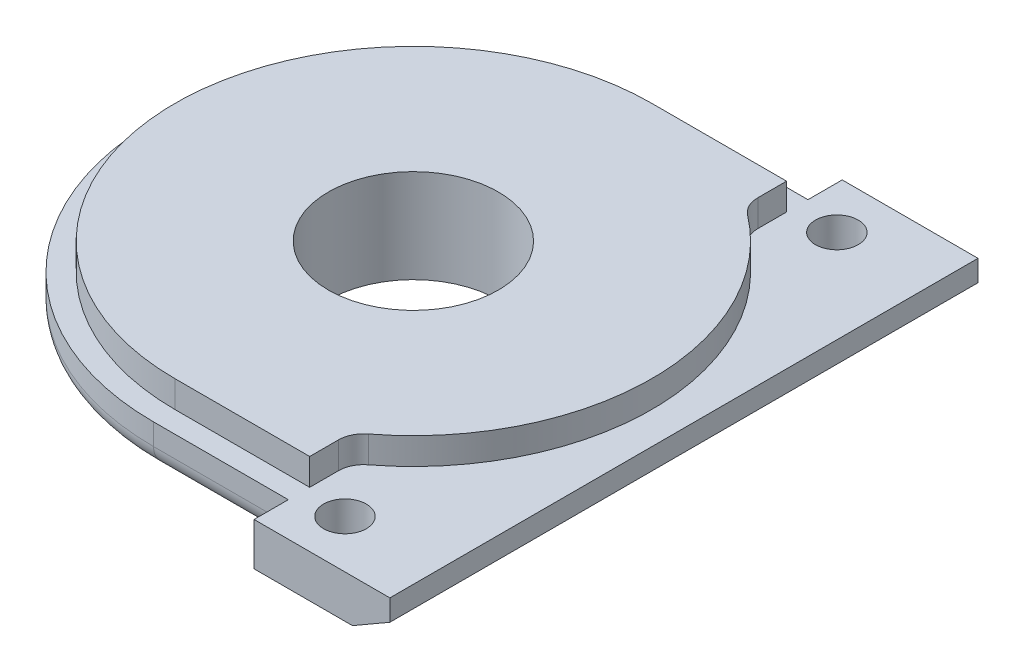
SolidWorks part; units mm, degrees
material "6061-T6 (SS)"
ref_plane "Front Plane" through (0, 0, 0) normal (0, 0, 1) x (1, 0, 0)
ref_plane "Top Plane" through (0, 0, 0) normal (0, 1, 0) x (1, 0, 0)
ref_plane "Right Plane" through (0, 0, 0) normal (1, 0, 0) x (0, 0, -1)
sketch "Sketch1" plane through (0, 0, 0) normal (0, 1, 0) x (1, 0, 0)
  line L0 (-13.2912, 20.8898) -> (-0.69, 20.8898)
  line L5 (-13.2912, -23.7056) -> (-0.69, -23.7056)
  line L7 (-0.69, -23.7056) -> (-0.69, -28.9079)
  line L8 (-0.69, -28.9079) -> (12.01, -28.9079)
  line L9 (-0.69, 20.8898) -> (-0.69, 26.0921)
  line L10 (12.01, -28.9079) -> (12.01, 26.0921)
  line L11 (12.01, 26.0921) -> (-0.69, 26.0921)
  arc A0 (-13.2912, 20.8898) -> (-13.2912, -23.7056) centre (-13.2912, -1.4079) ccw
extrude "Boss-Extrude1" add sketch "Sketch1" along normal blind 4
sketch "Sketch2" plane through (0, 4, 0) normal (0, 1, 0) x (1, 0, 0)
  line L4 (-13.2912, 20.8898) -> (-0.69, 20.8898)
  line L5 (-0.69, 20.8898) -> (-0.69, 16.9877)
  line L6 (-13.2912, -23.7056) -> (-0.69, -23.7056)
  line L7 (-0.69, -23.7056) -> (-0.69, -19.8035)
  arc A0 (-0.69, -19.8035) -> (-0.69, 16.9877) centre (-13.2912, -1.4079) ccw
  arc A1 (-13.2912, 20.8898) -> (-13.2912, -23.7056) centre (-13.2912, -1.4079) ccw
extrude "Boss-Extrude2" add sketch "Sketch2" along normal blind 2.5
sketch "Sketch3" plane through (0, 0, 0) normal (0, -1, 0) x (1, 0, 0)
  circle A0 centre (-13.2912, 1.4079) radius 7.95
  dimension "D1" = 15.9
extrude "Cut-Extrude1" cut sketch "Sketch3" against normal blind 9.25
sketch "Sketch4" plane through (0, 0, 0) normal (0, -1, 0) x (1, 0, 0)
  line L0 (3.31, -21.5921) -> (3.31, -26.0921) construction
  line L2 (12.01, -26.0921) -> (-0.69, -26.0921) construction
  line L3 (3.31, -26.0921) -> (-0.69, -26.0921) construction
  line L5 (3.31, 24.4079) -> (3.31, 28.9079) construction
  line L6 (-0.69, 28.9079) -> (12.01, 28.9079) construction
  line L7 (3.31, 28.9079) -> (-0.69, 28.9079) construction
  circle A0 centre (3.31, 24.4079) radius 2
  circle A1 centre (3.31, -21.5921) radius 2
  dimension "D1" = 4.5
  dimension "D2" = 4
  dimension "D4" = 4
  dimension "D3" = 4.5
extrude "Cut-Extrude2" cut sketch "Sketch4" against normal blind 9.25
sketch "Sketch5" plane through (0, 0, 0) normal (0, -1, 0) x (1, 0, 0)
  line L9 (-20.9172, 10.6082) -> (-24.2357, 16.3644)
  line L12 (-17.4459, 12.6124) -> (-20.7716, 18.3644)
  line L14 (-1.5104, 3.4121) -> (5.1338, 3.4079)
  line L17 (-1.5104, -0.5963) -> (5.1338, -0.5921)
  line L19 (-17.4459, -9.7966) -> (-20.7716, -15.5486)
  line L22 (-20.9172, -7.7924) -> (-24.2357, -13.5486)
  circle A2 centre (-13.2912, 1.4079) radius 11.95
  arc A3 (-1.5104, 3.4121) -> (-17.4459, 12.6124) centre (-13.2912, 1.4079) ccw
  circle A4 centre (-13.2912, 1.4079) radius 18.45
  circle A5 centre (-13.2912, 1.4079) radius 18.45
  circle A6 centre (-13.2912, 1.4079) radius 18.45
  circle A7 centre (-13.2912, 1.4079) radius 18.45
  arc A8 (-20.9172, 10.6082) -> (-20.9172, -7.7924) centre (-13.2912, 1.4079) ccw
  arc A9 (-17.4459, -9.7966) -> (-1.5104, -0.5963) centre (-13.2912, 1.4079) ccw
  point P14 (-13.2912, 1.4079)
  dimension "D1" = 4
  dimension "D2" = 10.5
  dimension "D3" = 3
extrude "Cut-Extrude3" cut sketch "Sketch5" against normal blind 3.25 contours A8 L9 A4 L22 | L14 A4 L12 A3 | A9 L19 A4 L17
fillet "Fillet1" radius 2.36 10 edges at (-20.9172, 1.625, 10.6082) (-20.9172, 1.625, -7.7924) (-24.1939, 1.625, -13.4761) (-24.1939, 1.625, 16.2919) (5.0501, 1.625, 3.4079) (-1.5104, 1.625, 3.4121) (-20.7297, 1.625, 18.2919) (-1.5104, 1.625, -0.5963) (5.0501, 1.625, -0.5922) (-20.7297, 1.625, -15.4761)
chamfer "Chamfer1" distance 3.5 angle 30 1 edges at (12.01, 0, 1.4079)
sketch "Sketch10" plane through (0, 0, 0) normal (0, -1, 0) x (1, 0, 0)
  line L2 (-0.69, -22.8898) -> (-13.2912, -22.8898)
  line L3 (-13.2912, 25.7056) -> (-0.69, 25.7056)
  line L4 (-0.69, -20.8898) -> (-13.2912, -20.8898)
  line L5 (-13.2912, 23.7056) -> (-0.69, 23.7056)
  line L6 (-0.69, -20.8898) -> (-13.2912, -20.8898)
  line L7 (-13.2912, 23.7056) -> (-0.69, 23.7056)
  line L8 (-0.69, 25.7056) -> (-0.69, 23.7056)
  line L9 (-0.69, -20.8898) -> (-0.69, -22.8898)
  arc A1 (-13.2912, 25.7056) -> (-13.2912, -22.8898) centre (-13.2912, 1.4079) ccw
  arc A2 (-13.2912, 23.7056) -> (-13.2912, -20.8898) centre (-13.2912, 1.4079) ccw
  arc A3 (-13.2912, 23.7056) -> (-13.2912, -20.8898) centre (-13.2912, 1.4079) ccw
  dimension "D1" = 0
  dimension "D2" = 2
extrude "Boss-Extrude4" add sketch "Sketch10" against normal blind 4
fillet "Fillet4" radius 2 3 edges at (-6.9906, 0, 25.7056) (-6.9906, 0, -22.8898) (-37.5889, 0, 1.4079)
sketch "Sketch11" plane through (0, 0, 0) normal (0, -1, 0) x (1, 0, 0)
  circle A1 centre (-13.2912, 1.4079) radius 11.95
extrude "Boss-Extrude5" add sketch "Sketch11" along normal blind 2.25
sketch "Sketch12" plane through (0, 0, 0) normal (0, 1, 0) x (1, 0, 0)
  circle A2 centre (-13.2912, -1.4079) radius 7.95
  circle A3 centre (-13.2912, -1.4079) radius 7.95
  dimension "D1" = 0
extrude "Cut-Extrude4" cut sketch "Sketch12" against normal blind 2.25
fillet "Fillet5" radius 2.38 2 edges at (-0.69, 5.25, -16.9877) (-0.69, 5.25, 19.8035)
